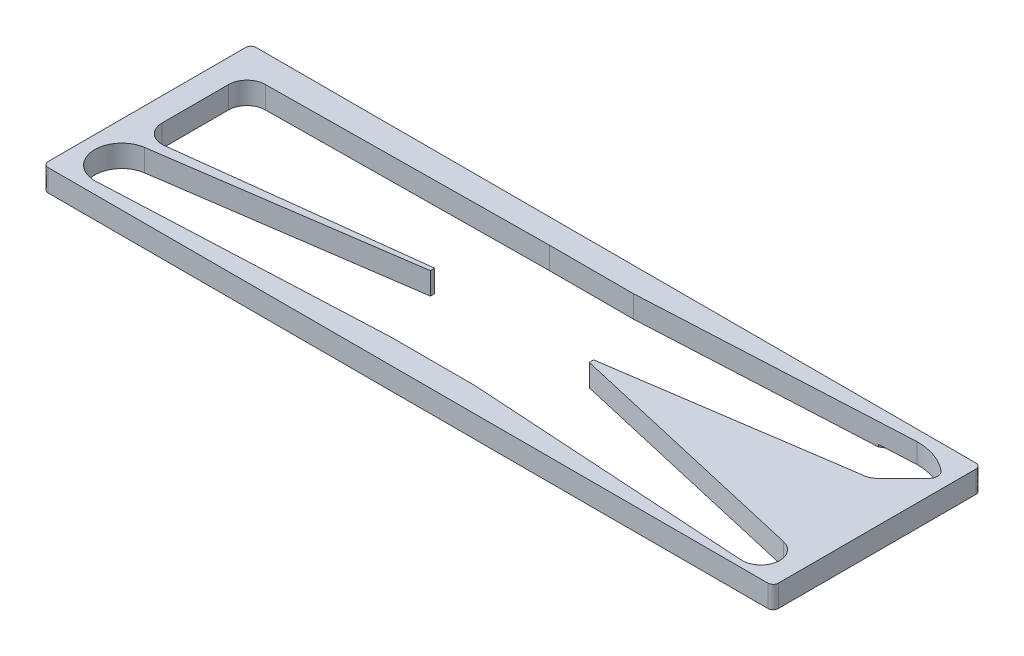
SolidWorks part; units mm, degrees
ref_plane "Front Plane" through (0, 0, 0) normal (0, 0, 1) x (1, 0, 0)
ref_plane "Top Plane" through (0, 0, 0) normal (0, 1, 0) x (1, 0, 0)
ref_plane "Right Plane" through (0, 0, 0) normal (1, 0, 0) x (0, 0, -1)
sketch "Sketch1" plane through (0, 0, 0) normal (0, 1, 0) x (1, 0, 0)
  line L1 (-850.9, 250.825) -> (850.9, 250.825)
  line L2 (-850.9, 250.825) -> (-850.9, -250.825)
  line L3 (-850.9, -250.825) -> (850.9, -250.825)
  line L4 (850.9, 250.825) -> (850.9, -250.825)
  line L5 (-850.9, 250.825) -> (850.9, -250.825) construction
  line L6 (-850.9, -250.825) -> (850.9, 250.825) construction
  point P0 (0, 0)
  dimension "D1" = 501.65
  dimension "D2" = 1701.8
sketch "Sketch2" plane through (0, 0, 0) normal (0, 1, 0) x (1, 0, 0)
  line L2 (183, 5) -> (719.0679, 84.7019)
  line L3 (719.074, 214.49) -> (97, 183)
  line L4 (-183, 5) -> (-183, -5)
  line L5 (183, 5) -> (183, -5)
  line L6 (97, 183) -> (-97, 183)
  line L7 (751.749, -224.1403) -> (97, -183)
  line L14 (183, -5) -> (183, 5) construction
  line L15 (183, -5) -> (764.1784, -138.6672)
  line L18 (-183, -5) -> (-757.9763, -88.3382)
  line L20 (-786.973, 133.7055) -> (-786.8656, -19.5095)
  line L23 (747.3521, 96.4177) -> (805.7401, 154.8057)
  line L29 (97, -183) -> (-97, -183)
  line L32 (-97, -183) -> (-749.0429, -212.2511)
  line L33 (841.2096, -6.1858) -> (840.1936, -6.1858) construction
  line L35 (719.074, 238.5946) -> (719.074, 239.6106) construction
  line L37 (-828.9373, -238.5946) -> (828.9373, -238.5946) construction
  line L38 (-840.1936, 227.3383) -> (-840.1936, -227.3383) construction
  line L39 (828.9373, 238.5946) -> (-828.9373, 238.5946) construction
  line L40 (840.1936, -227.3383) -> (840.1936, 227.3383) construction
  line L48 (-183, 5) -> (-183, -5) construction
  line L51 (-183, -5) -> (-97, -183) construction
  line L55 (828.9373, 239.6106) -> (-828.9373, 239.6106)
  line L56 (-841.2096, 227.3383) -> (-841.2096, -227.3383)
  line L57 (-828.9373, -239.6106) -> (828.9373, -239.6106)
  line L58 (841.2096, -227.3383) -> (841.2096, 227.3383)
  line L61 (-739.0896, -61.8836) -> (-183, 5)
  line L62 (-97, 183) -> (-744.7296, 176.3827)
  circle A11 centre (-749.0429, -149.9726) radius 38.1 construction
  arc A12 (719.0679, 84.7019) -> (747.3521, 96.4177) centre (719.0679, 124.7019) ccw
  arc A13 (805.7401, 154.8057) -> (804.1302, 184.5344) centre (791.598, 168.9478) ccw
  arc A14 (804.1302, 184.5344) -> (719.074, 214.49) centre (719.0679, 78.74) ccw
  arc A16 (-757.9763, -88.3382) -> (-749.0429, -212.2511) centre (-749.0429, -149.9726) ccw
  arc A17 (-744.7296, 176.3827) -> (-786.973, 133.7055) centre (-744.2936, 133.7055) ccw
  arc A18 (-786.8656, -19.5095) -> (-739.0896, -61.8836) centre (-744.1861, -19.5095) ccw
  arc A19 (751.749, -224.1403) -> (764.1784, -138.6672) centre (754.4663, -180.8952) ccw
  ellipse E8 centre (-828.5873, -226.9883) end of major axis (-836.917, -235.318) minor radius 11.43 (-840.1936, -227.3383) -> (-828.9373, -238.5946) ccw construction
  ellipse E9 centre (-828.5873, 226.9883) end of major axis (-836.917, 235.318) minor radius 11.43 (-828.9373, 238.5946) -> (-840.1936, 227.3383) ccw construction
  ellipse E10 centre (828.5873, 226.9883) end of major axis (836.917, 235.318) minor radius 11.43 (840.1936, 227.3383) -> (828.9373, 238.5946) ccw construction
  ellipse E11 centre (828.5873, -226.9883) end of major axis (836.917, -235.318) minor radius 11.43 (828.9373, -238.5946) -> (840.1936, -227.3383) ccw construction
  spline S4 degree 3 poles (-828.9373, 239.6106) (-830.5403, 239.6106) (-833.7901, 238.9792) (-837.8611, 236.2621) (-840.5782, 232.1911) (-841.2096, 228.9413) (-841.2096, 227.3383) knots -0.770319 -0.770319 -0.770319 -0.770319 -0.38516 0 0.38516 0.770319 0.770319 0.770319 0.770319
  spline S5 degree 3 poles (-841.2096, -227.3383) (-841.2096, -228.9413) (-840.5782, -232.1911) (-837.8611, -236.2621) (-833.7901, -238.9792) (-830.5403, -239.6106) (-828.9373, -239.6106) knots -0.770319 -0.770319 -0.770319 -0.770319 -0.38516 0 0.38516 0.770319 0.770319 0.770319 0.770319
  spline S6 degree 3 poles (828.9373, -239.6106) (830.5403, -239.6106) (833.7901, -238.9792) (837.8611, -236.2621) (840.5782, -232.1911) (841.2096, -228.9413) (841.2096, -227.3383) knots -0.770319 -0.770319 -0.770319 -0.770319 -0.38516 0 0.38516 0.770319 0.770319 0.770319 0.770319
  spline S7 degree 3 poles (841.2096, 227.3383) (841.2096, 228.9413) (840.5782, 232.1911) (837.8611, 236.2621) (833.7901, 238.9792) (830.5403, 239.6106) (828.9373, 239.6106) knots -0.770319 -0.770319 -0.770319 -0.770319 -0.38516 0 0.38516 0.770319 0.770319 0.770319 0.770319
  point P44 (754.4663, -180.8952)
extrude "Boss-Extrude3" add sketch "Sketch2" along normal blind 50.8
sketch "Sketch3" plane through (0, 0, 0) normal (0, -1, 0) x (1, 0, 0)
  line L4 (820.5662, -139.9796) -> (762.1782, -81.5916)
  line L5 (675.9576, -81.5916) -> (617.5696, -139.9796)
  line L6 (820.5662, -139.9796) -> (762.1782, -81.5916)
  line L7 (675.9576, -81.5916) -> (617.5696, -139.9796)
  circle A6 centre (754.5064, 181.8446) radius 44.45
  circle A7 centre (754.5064, 181.8446) radius 44.45
  arc A8 (762.1782, -81.5916) -> (675.9576, -81.5916) centre (719.0679, -124.7019) ccw
  arc A9 (617.5696, -139.9796) -> (620.8673, -200.8749) centre (646.5378, -168.9478) ccw
  arc A10 (620.8673, -200.8749) -> (817.2684, -200.8749) centre (719.0679, -78.74) ccw
  arc A11 (817.2684, -200.8749) -> (820.5662, -139.9796) centre (791.598, -168.9478) ccw
  arc A12 (762.1782, -81.5916) -> (675.9576, -81.5916) centre (719.0679, -124.7019) ccw
  arc A13 (617.5696, -139.9796) -> (620.8673, -200.8749) centre (646.5378, -168.9478) ccw
  arc A14 (620.8673, -200.8749) -> (817.2684, -200.8749) centre (719.0679, -78.74) ccw
  arc A15 (817.2684, -200.8749) -> (820.5662, -139.9796) centre (791.598, -168.9478) ccw
  dimension "D1" = 7.62
  dimension "D2" = 7.62
extrude "Cut-Extrude1" cut sketch "Sketch3" against normal blind 5.08
